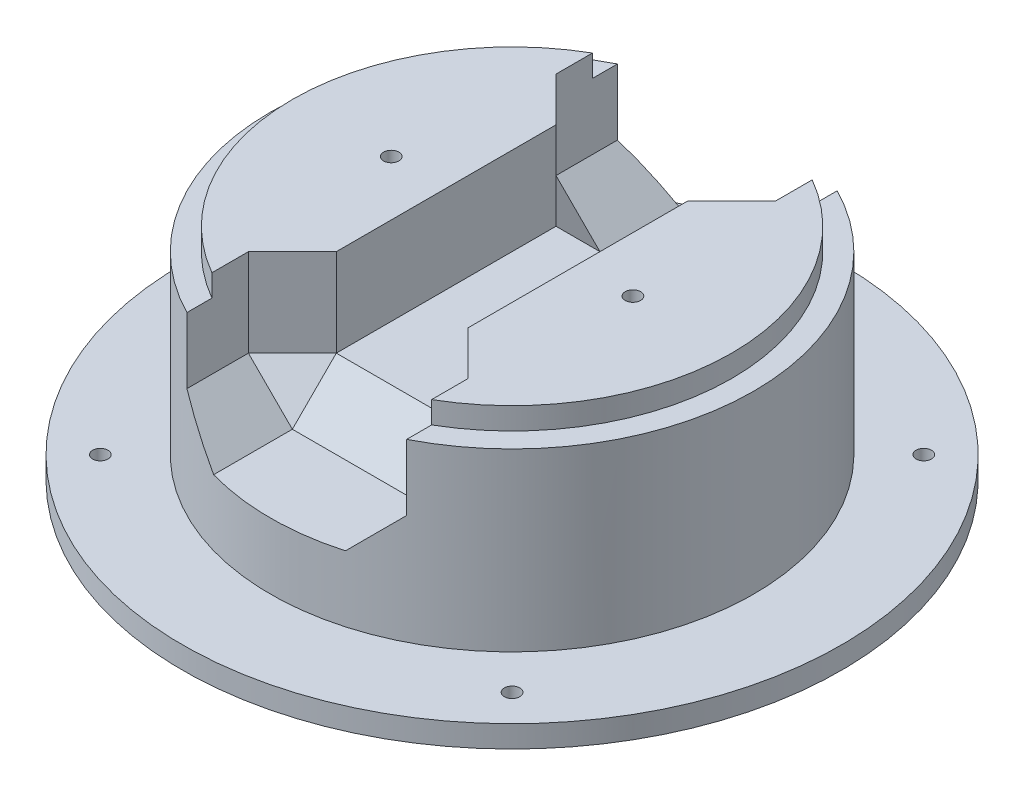
SolidWorks part; units mm, degrees
material "PBT General Purpose"
ref_plane "Front Plane" through (0, 0, 0) normal (0, 0, 1) x (1, 0, 0)
ref_plane "Top Plane" through (0, 0, 0) normal (0, 1, 0) x (1, 0, 0)
ref_plane "Right Plane" through (0, 0, 0) normal (1, 0, 0) x (0, 0, -1)
sketch "Sketch1" plane through (0, 0, 0) normal (0, 1, 0) x (1, 0, 0)
  circle A0 centre (0, 0) radius 55
  dimension "D1" = 110
extrude "Boss-Extrude1" add sketch "Sketch1" along normal blind 40
sketch "Sketch2" plane through (0, 0, 0) normal (0, -1, 0) x (1, 0, 0)
  circle A0 centre (0, 0) radius 75
  dimension "D1" = 150
extrude "Boss-Extrude2" add sketch "Sketch2" along normal blind 5
sketch "Sketch6" plane through (0, 40, 0) normal (0, 1, 0) x (1, 0, 0)
  circle A0 centre (0, 0) radius 50
  dimension "D1" = 100
extrude "Boss-Extrude3" add sketch "Sketch6" along normal blind 5
hole_wizard "Ø3.5 (3.5) Diameter Hole1" positions "Sketch5" profile "Sketch4" hole size "Ø3.5" standard "ISO"
sketch "Sketch5" plane through (-12.746, 45, -7.8689) normal (0, 1, 0) x (1, 0, 0)
  line L0 (-14.754, -7.8689) -> (40.246, -7.8689) construction
  point P1 (-14.754, -7.8689)
  point P2 (40.246, -7.8689)
  dimension "D1" = 55
sketch "Sketch4" plane through (-27.5, 45, 0) normal (1, 0, 0) x (0, 0, 1)
  line L0 (0, 0) -> (0, 11.0515)
  line L1 (0, 11.0515) -> (1.75, 10)
  line L2 (1.75, 10) -> (1.75, 0)
  line L5 (1.75, 0) -> (0, 0)
  line L10 (0, 11.0515) -> (-1.75, 10) construction
  line L11 (0, -6.35) -> (0, 107.95) construction
  dimension "Hole Dia." = 3.5
  dimension "Hole Depth" = 10
  dimension "Drill Angle" = 118
sketch "Sketch7" plane through (0, 45, 0) normal (0, 1, 0) x (1, 0, 0)
  line L0 (0, 25) -> (0, -25) construction
  line L1 (-25, 85) -> (25, 85)
  line L2 (-25, 85) -> (-25, 25)
  line L3 (-25, 25) -> (25, 25)
  line L4 (25, 85) -> (25, 25)
  line L5 (-25, 85) -> (25, 25) construction
  line L6 (-25, 25) -> (25, 85) construction
  line L7 (-25, -25) -> (25, -25)
  line L8 (-25, -25) -> (-25, -85)
  line L9 (-25, -85) -> (25, -85)
  line L10 (25, -25) -> (25, -85)
  line L11 (-25, -25) -> (25, -85) construction
  line L12 (-25, -85) -> (25, -25) construction
  circle A0 centre (0, 0) radius 55 construction
  circle A1 centre (0, 0) radius 55 construction
  point P0 (0, 55)
  point P9 (0, -55)
  dimension "D1" = 50
  dimension "D2" = 50
extrude "Cut-Extrude1" cut sketch "Sketch7" against normal blind 30
chamfer "Chamfer1" distance 10 angle 45 10 edges at (-25, 15, -36.9949) (25, 15, -36.9949) (25, 30, -25) (-25, 30, -25) (0, 15, -25) (-25, 15, 36.9949) (25, 15, 36.9949) (25, 30, 25) (-25, 30, 25) (0, 15, 25)
sketch "Sketch8" plane through (0, 45, 0) normal (0, 1, 0) x (1, 0, 0)
  line L1 (15, 25) -> (-15, 25)
  line L2 (15, 25) -> (15, -25)
  line L3 (15, -25) -> (-15, -25)
  line L4 (-15, 25) -> (-15, -25)
  line L5 (15, 25) -> (-15, -25) construction
  line L6 (15, -25) -> (-15, 25) construction
  point P0 (0, 0)
extrude "Cut-Extrude2" cut sketch "Sketch8" against normal blind 20
hole_wizard "Ø3.5 (3.5) Diameter Hole2" positions "Sketch10" profile "Sketch9" hole size "Ø3.5" standard "ISO"
sketch "Sketch10" plane through (0, 0, 0) normal (0, 1, 0) x (1, 0, 0)
  line L1 (-46.8458, 46.8458) -> (46.8458, 46.8458)
  line L2 (-46.8458, 46.8458) -> (-46.8458, -46.8458)
  line L3 (-46.8458, -46.8458) -> (46.8458, -46.8458)
  line L4 (46.8458, 46.8458) -> (46.8458, -46.8458)
  line L5 (-46.8458, 46.8458) -> (46.8458, -46.8458) construction
  line L6 (-46.8458, -46.8458) -> (46.8458, 46.8458) construction
  point P1 (0, 0)
  point P2 (46.8458, -46.8458)
  point P99 (-46.8458, 46.8458)
  point P100 (-46.8458, -46.8458)
  point P101 (46.8458, 46.8458)
  dimension "D1" = 132.5
sketch "Sketch9" plane through (0, 0, 0) normal (1, 0, 0) x (0, 0, 1)
  line L0 (0, 0) -> (0, 11.0515)
  line L1 (0, 11.0515) -> (1.75, 10)
  line L2 (1.75, 10) -> (1.75, 0)
  line L5 (1.75, 0) -> (0, 0)
  line L10 (0, 11.0515) -> (-1.75, 10) construction
  line L11 (0, -6.35) -> (0, 107.95) construction
  dimension "Hole Dia." = 3.5
  dimension "Hole Depth" = 10
  dimension "Drill Angle" = 118
